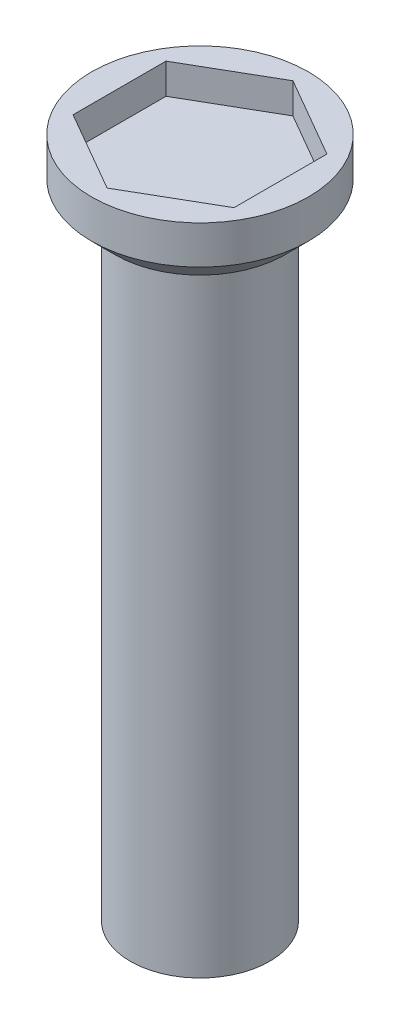
SolidWorks part; units mm, degrees
material "AISI 1015 Steel, Cold Drawn (SS)"
ref_plane "Front Plane" through (0, 0, 0) normal (0, 0, 1) x (1, 0, 0)
ref_plane "Top Plane" through (0, 0, 0) normal (0, 1, 0) x (1, 0, 0)
ref_plane "Right Plane" through (0, 0, 0) normal (1, 0, 0) x (0, 0, -1)
sketch "Sketch1" plane through (0, 0, 0) normal (0, 1, 0) x (1, 0, 0)
  circle A0 centre (0, 0) radius 2.25
  dimension "D1" = 4.5
extrude "Length" add sketch "Sketch1" along normal blind 20
sketch "Sketch2" plane through (0, 20, 0) normal (0, 1, 0) x (1, 0, 0)
  circle A0 centre (0, 0) radius 3.5
  dimension "D1" = 7
extrude "Cap" add sketch "Sketch2" along normal blind 2
chamfer "Chamfer" distance 0.762 angle 45 1 edges at (0, 20, 3.5)
sketch "Sketch3" plane through (0, 22, 0) normal (0, 1, 0) x (1, 0, 0)
  line L1 (0, 3) -> (-2.5981, 1.5)
  line L2 (-2.5981, 1.5) -> (-2.5981, -1.5)
  line L3 (-2.5981, -1.5) -> (0, -3)
  line L4 (0, -3) -> (2.5981, -1.5)
  line L5 (2.5981, -1.5) -> (2.5981, 1.5)
  line L6 (2.5981, 1.5) -> (0, 3)
  circle A0 centre (0, 0) radius 2.5981 construction
  dimension "D1" = 3
extrude "Hex" cut sketch "Sketch3" against normal blind 0.984
